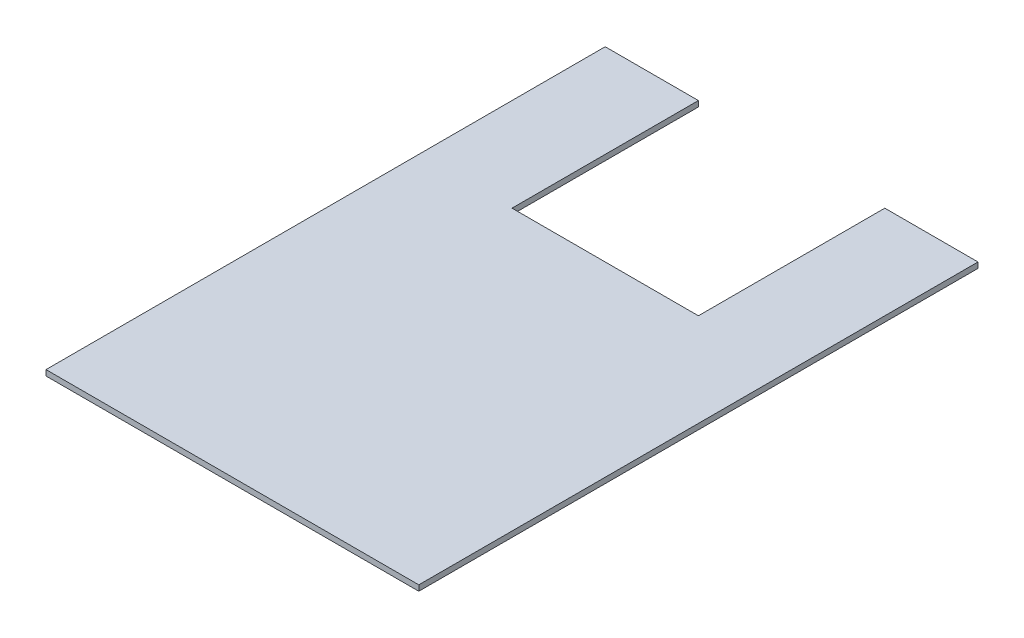
SolidWorks part; units mm, degrees
ref_plane "Front Plane" through (0, 0, 0) normal (0, 0, 1) x (1, 0, 0)
ref_plane "Top Plane" through (0, 0, 0) normal (0, 1, 0) x (1, 0, 0)
ref_plane "Right Plane" through (0, 0, 0) normal (1, 0, 0) x (0, 0, -1)
sketch "Sketch1" plane through (0, 0, 0) normal (0, 1, 0) x (1, 0, 0)
  line L1 (-100, 150) -> (100, 150)
  line L2 (-100, 150) -> (-100, -150)
  line L3 (-100, -150) -> (100, -150)
  line L4 (100, 150) -> (100, -150)
  line L5 (-100, 150) -> (100, -150) construction
  line L6 (-100, -150) -> (100, 150) construction
  point P0 (0, 0)
  dimension "D1" = 200
  dimension "D2" = 300
extrude "Boss-Extrude1" add sketch "Sketch1" along normal blind 3
sketch "Sketch3" plane through (0, 3, 0) normal (0, 1, 0) x (1, 0, 0)
  line L0 (0, 150) -> (50, 150)
  line L1 (100, 150) -> (-100, 150) construction
  line L2 (50, 150) -> (50, 50)
  line L3 (50, 50) -> (-50, 50)
  line L4 (-50, 50) -> (-50, 150)
  line L6 (-50, 150) -> (0, 150)
  line L7 (-50, 150) -> (50, 50) construction
  line L8 (0, 0) -> (0, 150) construction
  line L9 (50, 150) -> (-50, 50) construction
  dimension "D1" = 100
  dimension "D2" = 50
  dimension "D3" = 50
extrude "Cut-Extrude1" cut sketch "Sketch3" against normal through all contours L2 L3 L4 L6 L0
